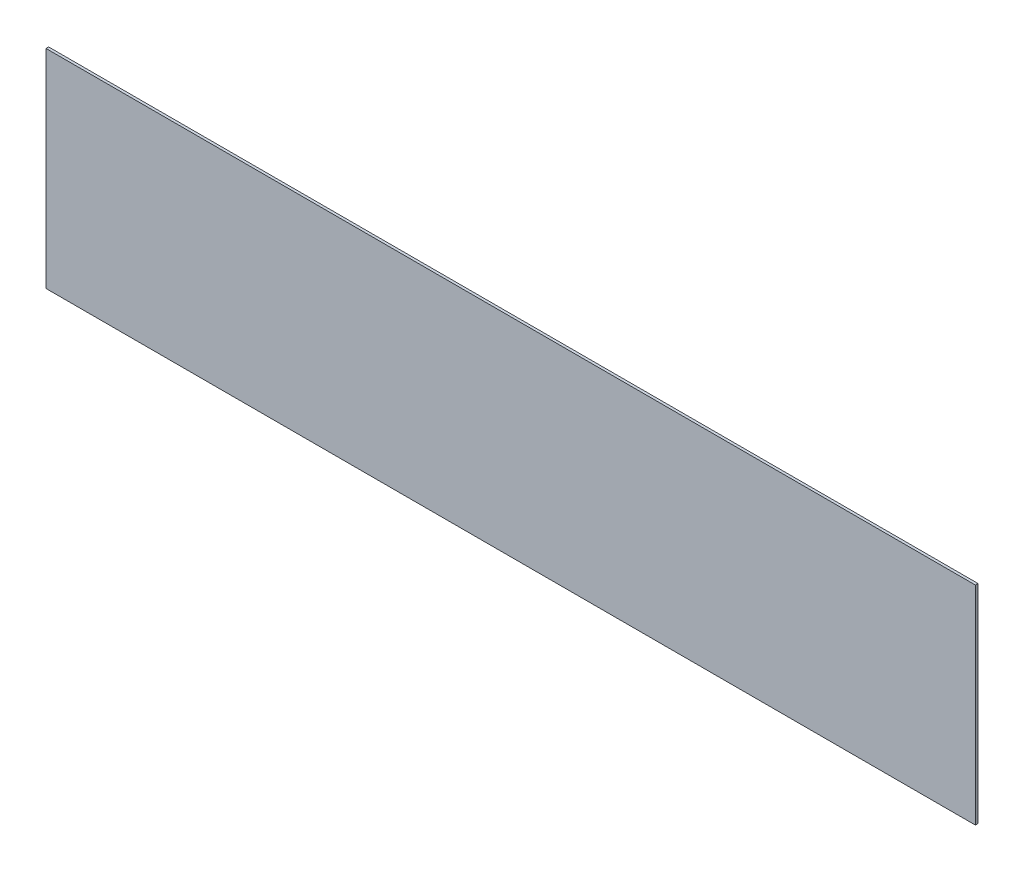
SolidWorks part; units mm, degrees
ref_plane "Front Plane" through (0, 0, 0) normal (0, 0, 1) x (1, 0, 0)
ref_plane "Top Plane" through (0, 0, 0) normal (0, 1, 0) x (1, 0, 0)
ref_plane "Right Plane" through (0, 0, 0) normal (1, 0, 0) x (0, 0, -1)
sketch "Sketch1" plane through (0, 0, 0) normal (0, 0, 1) x (1, 0, 0)
  line L1 (0, 0) -> (447, 0)
  line L2 (0, 0) -> (0, 100)
  line L3 (0, 100) -> (447, 100)
  line L4 (447, 0) -> (447, 100)
  dimension "D1" = 100
  dimension "D2" = 447
extrude "Boss-Extrude1" add sketch "Sketch1" along normal blind 1.27
